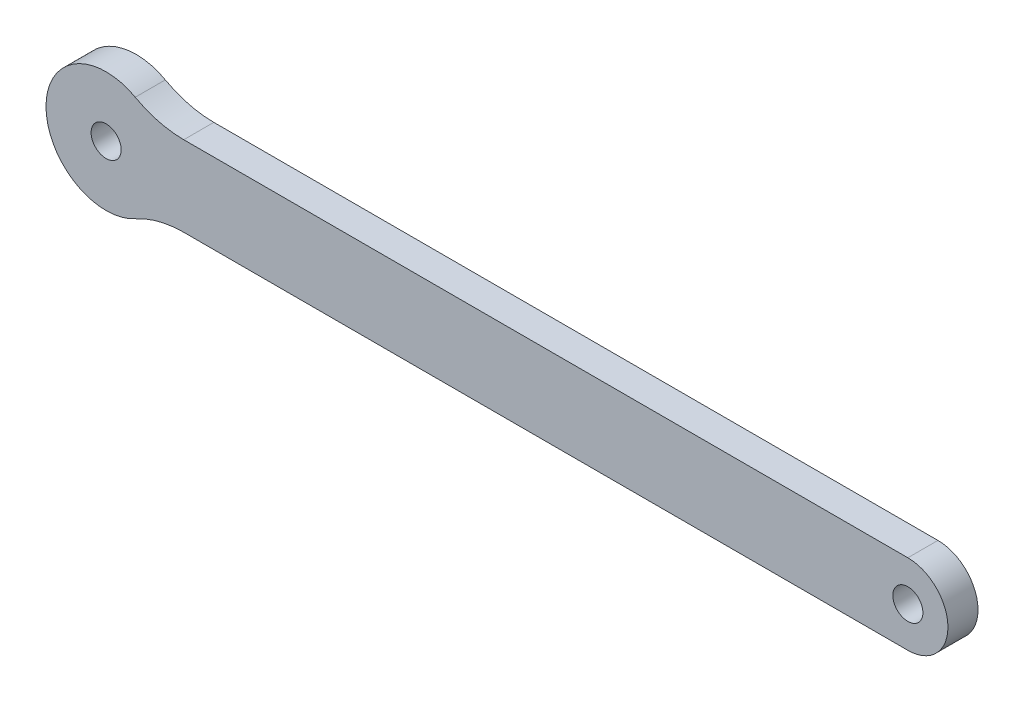
SolidWorks part; units mm, degrees
ref_plane "Plan de face" through (0, 0, 0) normal (0, 0, 1) x (1, 0, 0)
ref_plane "Plan de dessus" through (0, 0, 0) normal (0, 1, 0) x (1, 0, 0)
ref_plane "Plan de droite" through (0, 0, 0) normal (1, 0, 0) x (0, 0, -1)
sketch "Esquisse15" plane through (0, 0, 0) normal (0, 0, 1) x (1, 0, 0)
  line L0 (198.6471, 65.5642) -> (126.3931, 65.5642)
  line L2 (126.3931, 57.5642) -> (198.6471, 57.5642)
  circle A0 centre (118.6471, 61.5642) radius 1.5
  circle A1 centre (198.6471, 61.5642) radius 1.5
  arc A2 (121.5519, 66.8142) -> (121.5519, 56.3142) centre (118.6471, 61.5642) ccw
  arc A3 (198.6471, 57.5642) -> (198.6471, 65.5642) centre (198.6471, 61.5642) ccw
  arc A4 (121.5519, 56.3142) -> (126.3931, 57.5642) centre (126.3931, 47.5642) cw
  arc A5 (121.5519, 66.8142) -> (126.3931, 65.5642) centre (126.3931, 75.5642) ccw
  dimension "D1" = 3
  dimension "D2" = 3
  dimension "D3" = 12
  dimension "D4" = 8
  dimension "D5" = 10
  dimension "D6" = 80
extrude "Boss.-Extru.15" add sketch "Esquisse15" along normal blind 3 separate body
